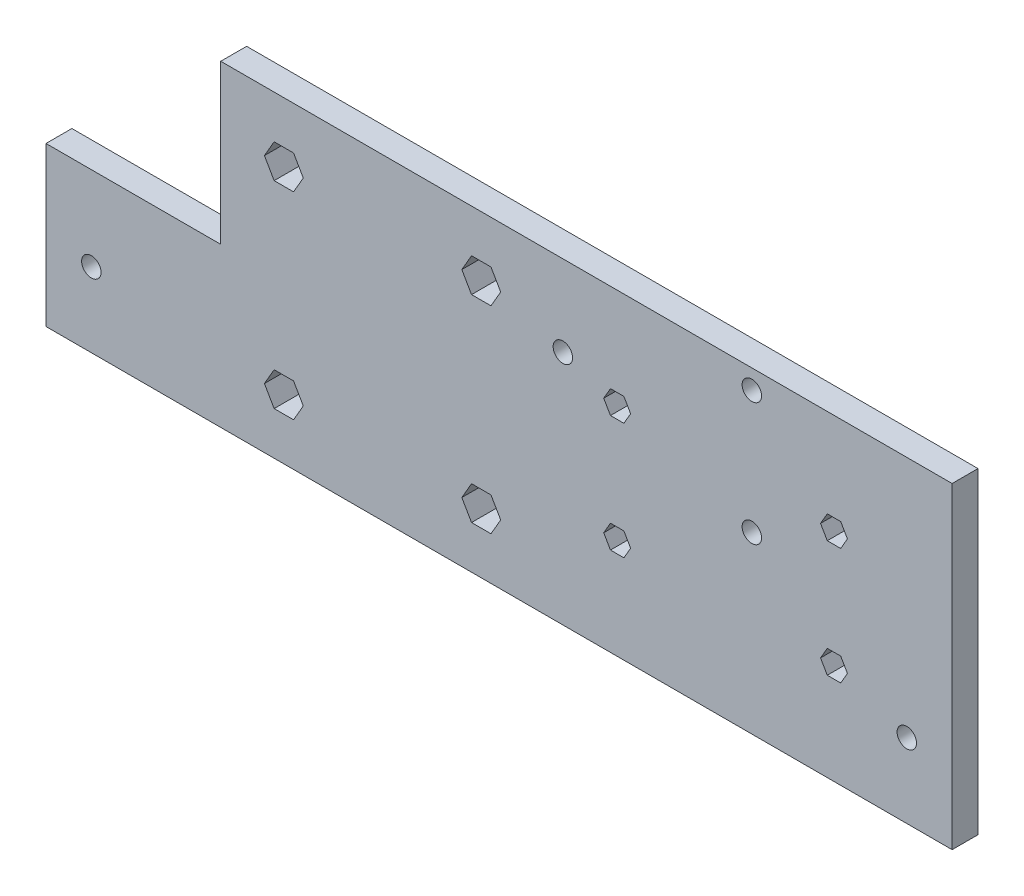
SolidWorks part; units mm, degrees
material "Balsa"
ref_plane "Front Plane" through (0, 0, 0) normal (0, 0, 1) x (1, 0, 0)
ref_plane "Top Plane" through (0, 0, 0) normal (0, 1, 0) x (1, 0, 0)
ref_plane "Right Plane" through (0, 0, 0) normal (1, 0, 0) x (0, 0, -1)
sketch "Sketch1" plane through (0, 0, 0) normal (0, 0, 1) x (1, 0, 0)
  line L0 (0, 0) -> (-40, 0)
  line L1 (0, 0) -> (100, 0)
  line L2 (-13, 24.5) -> (-13, 49)
  line L3 (-13, 49) -> (100, 49)
  line L4 (100, 0) -> (100, 49)
  line L5 (-40, 55) -> (-40, -6) construction
  line L6 (-40, 0) -> (-40, 24.5)
  line L7 (-40, 24.5) -> (-13, 24.5)
  dimension "D1" = 113
  dimension "D2" = 49
extrude "Boss-Extrude1" add sketch "Sketch1" along normal blind 4
sketch "Sketch2" plane through (0, 0, 4) normal (0, 0, 1) x (1, 0, 0)
  circle A0 centre (39.8574, 36.5) radius 1.5
  circle A1 centre (69.0574, 27) radius 1.5
  circle A2 centre (69.0574, 46) radius 1.5
  dimension "D1" = 3
extrude "Cut-Extrude1" cut sketch "Sketch2" against normal blind 4
sketch "Sketch4" plane through (0, 0, -4) normal (0, 0, -1) x (-1, 0, 0)
  line L0 (-100, 24.5) -> (13, 24.5) construction
  line L1 (-80.7108, 31.7) -> (-79.6715, 33.5)
  line L2 (-79.6715, 33.5) -> (-80.7108, 35.3)
  line L3 (-80.7108, 35.3) -> (-82.7892, 35.3)
  line L4 (-82.7892, 35.3) -> (-83.8285, 33.5)
  line L5 (-83.8285, 33.5) -> (-82.7892, 31.7)
  line L6 (-82.7892, 31.7) -> (-80.7108, 31.7)
  line L7 (-47.2108, 31.7) -> (-46.1715, 33.5)
  line L8 (-46.1715, 33.5) -> (-47.2108, 35.3)
  line L9 (-47.2108, 35.3) -> (-49.2892, 35.3)
  line L10 (-49.2892, 35.3) -> (-50.3285, 33.5)
  line L11 (-50.3285, 33.5) -> (-49.2892, 31.7)
  line L12 (-49.2892, 31.7) -> (-47.2108, 31.7)
  line L13 (-47.2108, 13.7) -> (-46.1715, 15.5)
  line L14 (-46.1715, 15.5) -> (-47.2108, 17.3)
  line L15 (-47.2108, 17.3) -> (-49.2892, 17.3)
  line L16 (-49.2892, 17.3) -> (-50.3285, 15.5)
  line L17 (-50.3285, 15.5) -> (-49.2892, 13.7)
  line L18 (-49.2892, 13.7) -> (-47.2108, 13.7)
  line L19 (-80.7108, 13.7) -> (-79.6715, 15.5)
  line L20 (-79.6715, 15.5) -> (-80.7108, 17.3)
  line L21 (-80.7108, 17.3) -> (-82.7892, 17.3)
  line L22 (-82.7892, 17.3) -> (-83.8285, 15.5)
  line L23 (-83.8285, 15.5) -> (-82.7892, 13.7)
  line L24 (-82.7892, 13.7) -> (-80.7108, 13.7)
  line L25 (-100, 0) -> (-100, 49) construction
  circle A0 centre (-48.25, 33.5) radius 1.8 construction
  circle A7 centre (-81.75, 33.5) radius 1.8 construction
  circle A8 centre (-48.25, 15.5) radius 1.8 construction
  circle A9 centre (-81.75, 15.5) radius 1.8 construction
  dimension "D1" = 18
  dimension "D4" = 3.6
  dimension "D2" = 33.5
extrude "Cut-Extrude5" cut sketch "Sketch4" against normal blind 34
sketch "Sketch5" plane through (0, 0, 0) normal (0, 0, -1) x (-1, 0, 0)
  line L0 (-100, 24.5) -> (40, 24.5) construction
  line L1 (-100, 0) -> (-100, 49) construction
  line L3 (4.7511, 37.15) -> (6.2522, 39.75)
  line L4 (6.2522, 39.75) -> (4.7511, 42.35)
  line L5 (4.7511, 42.35) -> (1.7489, 42.35)
  line L6 (1.7489, 42.35) -> (0.2478, 39.75)
  line L7 (0.2478, 39.75) -> (1.7489, 37.15)
  line L8 (1.7489, 37.15) -> (4.7511, 37.15)
  line L9 (-25.7489, 37.15) -> (-24.2478, 39.75)
  line L10 (-24.2478, 39.75) -> (-25.7489, 42.35)
  line L11 (-25.7489, 42.35) -> (-28.7511, 42.35)
  line L12 (-28.7511, 42.35) -> (-30.2522, 39.75)
  line L13 (-30.2522, 39.75) -> (-28.7511, 37.15)
  line L14 (-28.7511, 37.15) -> (-25.7489, 37.15)
  line L15 (-25.7489, 6.65) -> (-24.2478, 9.25)
  line L16 (-24.2478, 9.25) -> (-25.7489, 11.85)
  line L17 (-25.7489, 11.85) -> (-28.7511, 11.85)
  line L18 (-28.7511, 11.85) -> (-30.2522, 9.25)
  line L19 (-30.2522, 9.25) -> (-28.7511, 6.65)
  line L20 (-28.7511, 6.65) -> (-25.7489, 6.65)
  line L21 (4.7511, 6.65) -> (6.2522, 9.25)
  line L22 (6.2522, 9.25) -> (4.7511, 11.85)
  line L23 (4.7511, 11.85) -> (1.7489, 11.85)
  line L24 (1.7489, 11.85) -> (0.2478, 9.25)
  line L25 (0.2478, 9.25) -> (1.7489, 6.65)
  line L26 (1.7489, 6.65) -> (4.7511, 6.65)
  circle A4 centre (3.25, 39.75) radius 2.6 construction
  circle A5 centre (-27.25, 39.75) radius 2.6 construction
  circle A6 centre (-27.25, 9.25) radius 2.6 construction
  circle A7 centre (3.25, 9.25) radius 2.6 construction
  point P1 (5.5017, 38.45)
  dimension "D1" = 5.2
extrude "Cut-Extrude6" cut sketch "Sketch5" against normal blind 34
sketch "Sketch6" plane through (0, 0, 4) normal (0, 0, 1) x (1, 0, 0)
  circle A0 centre (-33, 11.5) radius 1.5
  circle A1 centre (93, 11.5) radius 1.5
extrude "Cut-Extrude7" cut sketch "Sketch6" against normal blind 10
